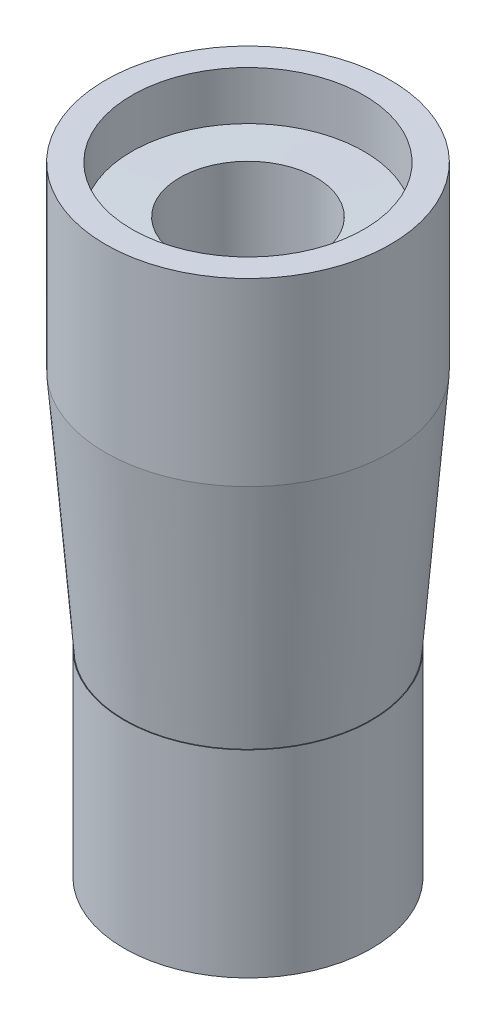
SolidWorks part; units mm, degrees
ref_plane "Front Plane" through (0, 0, 0) normal (0, 0, 1) x (1, 0, 0)
ref_plane "Top Plane" through (0, 0, 0) normal (0, 1, 0) x (1, 0, 0)
ref_plane "Right Plane" through (0, 0, 0) normal (1, 0, 0) x (0, 0, -1)
sketch "Sketch1" plane through (0, 0, 0) normal (0, 0, 1) x (1, 0, 0)
  line L3 (-21.7387, -13.0752) -> (-21.7387, -16.9873)
  line L7 (-24.1496, -1.9873) -> (-25.6121, 16.3263)
  line L8 (-25.6121, 16.3263) -> (-25.6121, 26.3263)
  line L9 (-14.7971, 26.4248) -> (-14.7971, -17.3951) construction
  line L15 (-24.1496, -1.9873) -> (-24.1996, -1.9873)
  line L16 (-24.1996, -1.9873) -> (-24.1996, -16.9873)
  line L18 (-24.1996, -16.9873) -> (-21.7387, -16.9873)
  line L25 (-25.6121, 26.3263) -> (-25.6121, 30.0163)
  line L26 (-25.6121, 30.0163) -> (-23.6121, 30.0163)
  line L27 (-23.6121, 30.0163) -> (-23.6121, 26.3263)
  line L29 (-14.7971, 26.4248) -> (-19.9721, 26.4248) construction
  line L30 (-23.6121, 26.3263) -> (-19.9721, 26.4248)
  line L31 (-19.9721, 26.4248) -> (-19.9721, -13.0752)
  line L32 (-19.9721, -13.0752) -> (-21.7387, -13.0752)
  point P12 (-25.6121, 21.3263)
  dimension "D1" = 2
  dimension "D4" = 90
  dimension "D5" = 90
  dimension "D6" = 5.175
  dimension "D7" = 39.5
  dimension "D8" = 10.815
  dimension "D9" = 0.05
  dimension "D10" = 90
  dimension "D11" = 3.69
revolve "Revolve1" add sketch "Sketch1" angle 360 about L9
